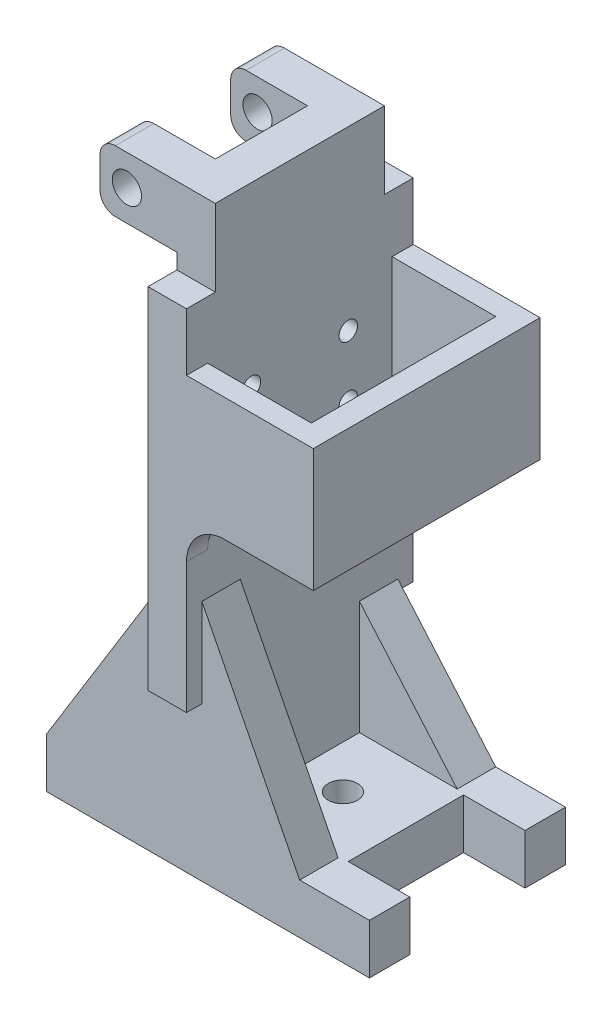
SolidWorks part; units mm, degrees
ref_plane "Plan de face" through (0, 0, 0) normal (0, 0, 1) x (1, 0, 0)
ref_plane "Plan de dessus" through (0, 0, 0) normal (0, 1, 0) x (1, 0, 0)
ref_plane "Plan de droite" through (0, 0, 0) normal (1, 0, 0) x (0, 0, -1)
sketch "Esquisse1" plane through (0, 0, 0) normal (0, 1, 0) x (1, 0, 0)
  line L1 (-21, -12.75) -> (21, -12.75)
  line L2 (-21, -12.75) -> (-21, 12.75)
  line L3 (-21, 12.75) -> (21, 12.75)
  line L4 (21, -12.75) -> (21, 12.75)
  line L5 (-21, -12.75) -> (21, 12.75) construction
  line L6 (-21, 12.75) -> (21, -12.75) construction
  point P0 (0, 0)
  dimension "D1" = 42
  dimension "D2" = 25.5
extrude "Boss.-Extru.1" add sketch "Esquisse1" along normal blind 6.5
sketch "Esquisse2" plane through (0, 0, 0) normal (0, 1, 0) x (1, 0, 0)
  line L0 (-21, 0) -> (21, 0) construction
  line L1 (-21, 12.75) -> (-21, -12.75) construction
  line L2 (21, -12.75) -> (21, 12.75) construction
  line L3 (0, 12.75) -> (0, 0) construction
  line L4 (-29, -7.5) -> (-13, -7.5)
  line L5 (-29, -7.5) -> (-29, 7.5)
  line L6 (-29, 7.5) -> (-13, 7.5)
  line L7 (-13, -7.5) -> (-13, 7.5)
  line L8 (-29, -7.5) -> (-13, 7.5) construction
  line L9 (-29, 7.5) -> (-13, -7.5) construction
  line L10 (21, 12.75) -> (-21, 12.75) construction
  line L11 (29, 7.5) -> (13, 7.5)
  line L12 (13, -7.5) -> (13, 7.5)
  line L13 (29, -7.5) -> (13, -7.5)
  line L14 (29, -7.5) -> (29, 7.5)
  dimension "D1" = 16
  dimension "D2" = 15
extrude "Enlèv. mat.-Extru.1" cut sketch "Esquisse2" along normal blind 10
sketch "Esquisse3" plane through (0, 6.5, 0) normal (0, 1, 0) x (1, 0, 0)
  line L0 (21.2, 0) -> (-3.3, 0) construction
  line L1 (21, 12.75) -> (-21, 12.75) construction
  line L2 (-5.8, -12.75) -> (-0.8, -12.75)
  line L3 (-5.8, -12.75) -> (-5.8, 12.75)
  line L4 (-5.8, 12.75) -> (-0.8, 12.75)
  line L5 (-0.8, -12.75) -> (-0.8, 12.75)
  line L6 (-5.8, -12.75) -> (-0.8, 12.75) construction
  line L7 (-5.8, 12.75) -> (-0.8, -12.75) construction
  dimension "D1" = 24.5
  dimension "D2" = 5
extrude "Boss.-Extru.2" add sketch "Esquisse3" along normal blind 13.5
sketch "Esquisse4" plane through (-0.8, 0, 0) normal (1, 0, 0) x (0, 0, -1)
  line L0 (0, 0) -> (0, 20) construction
  line L1 (-12.75, 20) -> (12.75, 20) construction
  line L2 (-12.75, 52.5) -> (12.75, 52.5) construction
  line L3 (-12.75, 20) -> (-12.75, 6.5) construction
  line L4 (12.75, 20) -> (12.75, 6.5) construction
  line L5 (12.75, 44.5) -> (-12.75, 44.5) construction
  line L6 (-6.3, 56.7126) -> (-6.3, 0) construction
  line L7 (6.3, 0) -> (6.3, 57.458) construction
  line L8 (-6.3, 0) -> (6.3, 0) construction
  circle A0 centre (-6.3, 52.5) radius 1.2
  circle A1 centre (6.3, 52.5) radius 1.2
  circle A2 centre (6.3, 44.5) radius 1.2
  circle A3 centre (-6.3, 44.5) radius 1.2
  dimension "D4" = 2.4
  dimension "D5" = 2.4
  dimension "D6" = 2.4
  dimension "D7" = 2.4
  dimension "D1" = 44.5
  dimension "D2" = 8
  dimension "D3" = 12.6
sketch "Esquisse5" plane through (0, 20, 0) normal (0, 1, 0) x (1, 0, 0)
  line L0 (-0.8, 0) -> (33.0123, 0) construction
  line L1 (-0.8, 12) -> (-0.8, -12) construction
  line L2 (-0.8, -12.75) -> (-0.8, 12.75) construction
  line L3 (-0.8, 12) -> (12.7, 12) construction
  line L4 (-0.8, 14.75) -> (-0.8, 12)
  line L5 (-0.8, 12) -> (12.7, 12)
  line L6 (12.7, 12) -> (12.7, -12)
  line L7 (12.7, -12) -> (-0.8, -12)
  line L8 (-0.8, -12) -> (-0.8, -14.75)
  line L9 (-0.8, -14.75) -> (15.7, -14.75)
  line L11 (15.7, -14.75) -> (15.7, 14.75)
  line L13 (15.7, 14.75) -> (-0.8, 14.75)
  dimension "D1" = 24
  dimension "D2" = 13.5
  dimension "D3" = 3
  dimension "D4" = 2.75
  dimension "D5" = 2.75
sketch "Esquisse6" plane through (0, 20, 0) normal (0, 1, 0) x (1, 0, 0)
  line L0 (-3.3, 12.75) -> (-3.3, 0) construction
  line L1 (-5.8, -14.75) -> (-0.8, -14.75)
  line L2 (-5.8, -14.75) -> (-5.8, 14.75)
  line L3 (-5.8, 14.75) -> (-0.8, 14.75)
  line L4 (-0.8, -14.75) -> (-0.8, 14.75)
  line L5 (-5.8, -14.75) -> (-0.8, 14.75) construction
  line L6 (-5.8, 14.75) -> (-0.8, -14.75) construction
  line L7 (-0.8, 12.75) -> (-5.8, 12.75) construction
  line L8 (-3.3, 0) -> (-0.8, 0) construction
  line L9 (-0.8, 0) -> (33.0123, 0) construction
  line L10 (-0.8, 12) -> (-0.8, -12) construction
  point P0 (-3.3, 0)
  dimension "D1" = 29.5
  dimension "D2" = 5
extrude "Boss.-Extru.3" add sketch "Esquisse6" along normal blind 45.5 contours L3 L4 L1 L2
extrude "Enlèv. mat.-Extru.3" cut sketch "Esquisse4" against normal blind 45.5 contours A3 | A0 | A1 | A2
extrude "Boss.-Extru.4" add sketch "Esquisse5" along normal blind 16 from offset 22 contours L6 L7 L8 L9 L11 L13 L4 L5
fillet "Congé2" radius 5 2 edges at (-0.8, 42, -13.375) (-0.8, 42, 13.375)
sketch "Esquisse9" plane through (0, 0, 12.75) normal (0, 0, 1) x (1, 0, 0)
  line L0 (-0.8, 37) -> (-0.8, 20) construction
  line L1 (-0.8, 6.5) -> (21, 6.5) construction
  line L2 (-0.8, 22.0344) -> (-0.8, 6.5)
  line L3 (-0.8, 6.5) -> (11.9261, 6.5)
  line L4 (-0.8, 22.0344) -> (-0.8, 31.5381)
  line L5 (-0.8, 37) -> (-0.8, 20) construction
  line L6 (-0.8, 31.5381) -> (11.9261, 6.5)
extrude "Boss.-Extru.5" add sketch "Esquisse9" against normal blind 5
sketch "Esquisse10" plane through (0, 6.5, 0) normal (0, 1, 0) x (1, 0, 0)
  circle A1 centre (-9.1997, 0) radius 1.9
  circle A2 centre (4.8003, 0) radius 1.9
  dimension "D1" = 2
  dimension "D2" = 3.8
extrude "Enlèv. mat.-Extru.5" cut sketch "Esquisse10" against normal blind 17
sketch "Esquisse11" plane through (-5.8, 0, 0) normal (-1, 0, 0) x (0, 0, 1)
  line L0 (-6.3, 52.5) -> (6.3, 52.5) construction
  line L1 (0, 52.5) -> (0, 40.05) construction
  line L3 (-10, 35.05) -> (10, 35.05)
  line L4 (-10, 35.05) -> (-10, 40.05)
  line L5 (-10, 40.05) -> (10, 40.05)
  line L6 (10, 35.05) -> (10, 40.05)
  line L7 (-10, 35.05) -> (10, 40.05) construction
  line L8 (-10, 40.05) -> (10, 35.05) construction
  point P7 (0, 37.55)
  dimension "D1" = 12.45
  dimension "D2" = 20
  dimension "D3" = 5
extrude "Boss.-Extru.6" add sketch "Esquisse11" along normal blind 4
sketch "Esquisse12" plane through (0, 0, -12.75) normal (0, 0, -1) x (-1, 0, 0)
  line L0 (0.8, 21.3042) -> (-11.9261, 6.5)
  line L1 (0.8, 31.5381) -> (0.8, 6.5) construction
  line L2 (-21, 6.5) -> (0.8, 6.5) construction
  line L3 (0.8, 6.5) -> (-11.9261, 6.5) construction
  line L4 (-11.9261, 6.5) -> (0.8, 6.5)
  line L5 (0.8, 6.5) -> (0.8, 21.3042)
extrude "Boss.-Extru.7" add sketch "Esquisse12" against normal blind 5
sketch "Esquisse13" plane through (0, 0, 12.75) normal (0, 0, 1) x (1, 0, 0)
  line L0 (-21, 6.5) -> (-5.8, 31.179)
  line L1 (-5.8, 65.5) -> (-5.8, 20) construction
  line L2 (-21, 6.5) -> (-5.8, 6.5)
  line L3 (-5.8, 6.5) -> (-5.8, 31.179)
extrude "Boss.-Extru.8" add sketch "Esquisse13" against normal blind 5.25
pattern_linear "Répétition linéaire1" count 2 spacing 20.25 along (0, 0, -1) of "Boss.-Extru.8"
sketch "Esquisse15" plane through (0, 65.5, 0) normal (0, 1, 0) x (1, 0, 0)
  line L0 (-0.8, -7.75) -> (-0.8, 7.75) construction
  line L1 (-5.8, -11) -> (-0.8, -11)
  line L2 (-5.8, -11) -> (-5.8, 11)
  line L3 (-5.8, 11) -> (-0.8, 11)
  line L4 (-0.8, -11) -> (-0.8, 11)
  line L5 (-5.8, -11) -> (-0.8, 11) construction
  line L6 (-5.8, 11) -> (-0.8, -11) construction
  line L7 (-5.8, 0) -> (-0.8, 0)
  point P0 (-3.3, 0)
  point P9 (0, 0)
  dimension "D1" = 22
extrude "Boss.-Extru.9" add sketch "Esquisse15" along normal blind 10 contours L2 L1 L4 L3
sketch "Esquisse16" plane through (0, 0, 11) normal (0, 0, 1) x (1, 0, 0)
  line L0 (-5.8, 75.5) -> (-5.8, 67.5)
  line L1 (-5.8, 75.5) -> (-13.8, 75.5)
  line L2 (-5.8, 67.5) -> (-13.8, 67.5)
  line L3 (-15.8, 73.5) -> (-15.8, 69.5)
  line L5 (-15.8, 71.5) -> (-5.8, 71.5) construction
  arc A0 (-13.8, 67.5) -> (-15.8, 69.5) centre (-13.8, 69.5) cw
  arc A1 (-13.8, 75.5) -> (-15.8, 73.5) centre (-13.8, 73.5) ccw
  circle A2 centre (-12.3, 71.5) radius 1.9
  point P7 (-15.8, 67.5)
  point P10 (-15.8, 75.5)
  point P13 (-10.8, 71.5)
  point P14 (0, 0)
  point P17 (-11.2461, 71.5)
  dimension "D2" = 2
  dimension "D4" = 3.8
  dimension "D5" = 3.5
  dimension "D1" = 10
  dimension "D3" = 8
extrude "Boss.-Extru.10" add sketch "Esquisse16" against normal blind 5
pattern_linear "Répétition linéaire2" count 2 spacing 17 along (0, 0, -1) of "Boss.-Extru.10"
